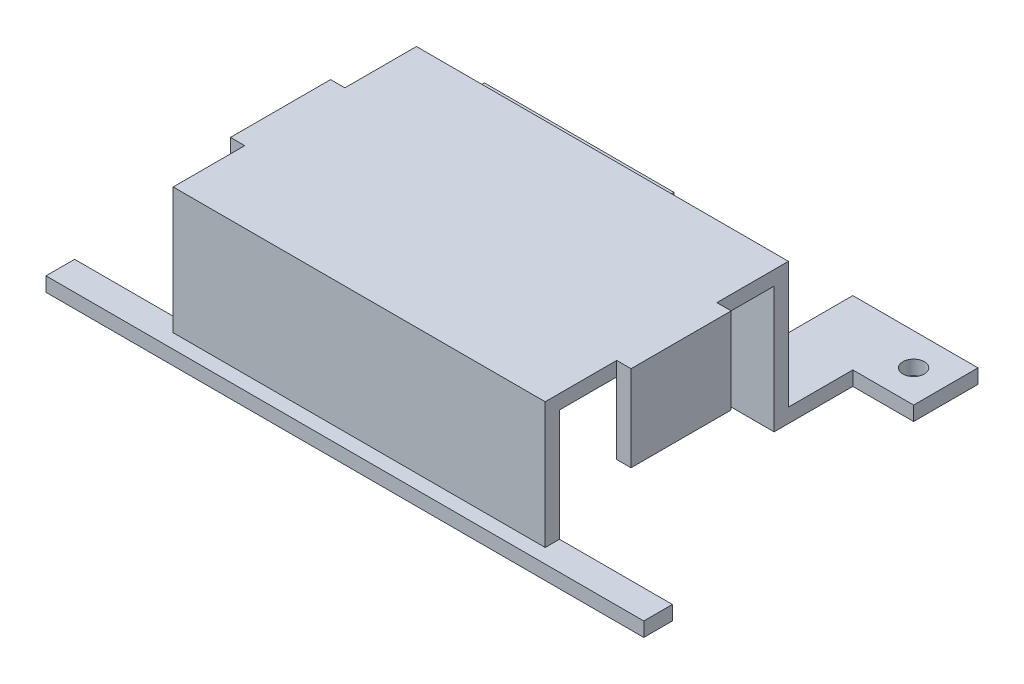
SolidWorks part; units mm, degrees
ref_plane "Front Plane" through (0, 0, 0) normal (0, 0, 1) x (1, 0, 0)
ref_plane "Top Plane" through (0, 0, 0) normal (0, 1, 0) x (1, 0, 0)
ref_plane "Right Plane" through (0, 0, 0) normal (1, 0, 0) x (0, 0, -1)
sketch "Sketch1" plane through (0, 0, 0) normal (0, 1, 0) x (1, 0, 0)
  line L1 (0, 0) -> (52, 0)
  line L2 (0, 0) -> (0, 34)
  line L3 (0, 34) -> (52, 34)
  line L4 (52, 0) -> (52, 34)
  dimension "D1" = 52
  dimension "D2" = 34
extrude "Boss-Extrude1" add sketch "Sketch1" along normal blind 19.65
sketch "Sketch2" plane through (0, 0, 0) normal (0, -1, 0) x (-1, 0, 0)
  line L0 (-52, 0) -> (-52, 34) construction
  line L1 (-52, 2) -> (0, 2)
  line L2 (-52, 2) -> (-52, 32)
  line L3 (-52, 32) -> (0, 32)
  line L4 (0, 2) -> (0, 32)
  line L5 (0, 34) -> (0, 0) construction
  line L6 (0, 0) -> (-52, 0) construction
  line L7 (-52, 34) -> (0, 34) construction
  dimension "D1" = 2
  dimension "D2" = 2
extrude "Cut-Extrude1" cut sketch "Sketch2" against normal blind 17.65
sketch "Sketch3" plane through (0, 0, -34) normal (0, 0, -1) x (-1, 0, 0)
  line L1 (-52, 0) -> (-43, 0)
  line L2 (-52, 0) -> (-52, 2)
  line L3 (-52, 2) -> (-43, 2)
  line L4 (-43, 0) -> (-43, 2)
  line L5 (0, 0) -> (-18, 0)
  line L6 (0, 0) -> (0, 2)
  line L7 (0, 2) -> (-18, 2)
  line L8 (-18, 0) -> (-18, 2)
  dimension "D1" = 9
  dimension "D2" = 2
  dimension "D3" = 18
  dimension "D4" = 2
extrude "Boss-Extrude2" add sketch "Sketch3" along normal blind 18
sketch "Sketch4" plane through (52, 0, 0) normal (1, 0, 0) x (0, 0, -1)
  line L0 (52, 2) -> (52, 0) construction
  line L1 (34, 2) -> (52, 2)
  line L2 (34, 2) -> (34, 0)
  line L3 (34, 0) -> (52, 0)
  line L4 (52, 2) -> (52, 0)
  line L5 (32, 0) -> (52, 0) construction
extrude "Boss-Extrude3" add sketch "Sketch4" along normal blind 8.5
sketch "Sketch5" plane through (0, 0, 0) normal (-1, 0, 0) x (0, 0, 1)
  line L1 (-34, 2) -> (-52, 2)
  line L2 (-34, 2) -> (-34, 0)
  line L3 (-34, 0) -> (-52, 0)
  line L4 (-52, 2) -> (-52, 0)
extrude "Boss-Extrude4" add sketch "Sketch5" along normal blind 8.5
sketch "Sketch6" plane through (0, 2, 0) normal (0, 1, 0) x (1, 0, 0)
  line L0 (-8.5, 34) -> (-8.5, 52) construction
  line L1 (-8.5, 52) -> (18, 52) construction
  line L2 (43, 52) -> (60.5, 52) construction
  line L3 (60.5, 52) -> (60.5, 34) construction
  circle A0 centre (56, 47.5) radius 1.5
  circle A1 centre (-4, 47.5) radius 1.5
  dimension "D1" = 3
  dimension "D2" = 3
  dimension "D3" = 4.5
  dimension "D4" = 4.5
  dimension "D5" = 4.5
  dimension "D6" = 4.5
extrude "Cut-Extrude2" cut sketch "Sketch6" against normal through all
sketch "Sketch7" plane through (0, 0, 0) normal (0, 0, 1) x (1, 0, 0)
  line L0 (0, 19.65) -> (0, 0) construction
  line L1 (0, 2) -> (52, 2)
  line L2 (0, 2) -> (0, 0)
  line L3 (0, 0) -> (52, 0)
  line L4 (52, 2) -> (52, 0)
  dimension "D1" = 2
extrude "Boss-Extrude5" add sketch "Sketch7" along normal blind 2
sketch "Sketch8" plane through (0, 0, 0) normal (-1, 0, 0) x (0, 0, 1)
  line L0 (-2, 0) -> (2, 0) construction
  line L1 (2, 2) -> (-2, 2)
  line L2 (2, 2) -> (2, 0)
  line L3 (2, 0) -> (-2, 0)
  line L4 (-2, 2) -> (-2, 0)
extrude "Boss-Extrude6" add sketch "Sketch8" along normal blind 15.78
sketch "Sketch9" plane through (52, 0, 0) normal (1, 0, 0) x (0, 0, -1)
  line L1 (-2, 2) -> (2, 2)
  line L2 (-2, 2) -> (-2, 0)
  line L3 (-2, 0) -> (2, 0)
  line L4 (2, 2) -> (2, 0)
extrude "Boss-Extrude7" add sketch "Sketch9" along normal blind 15.78
sketch "Sketch11" plane through (-8.5, 0, 0) normal (-1, 0, 0) x (0, 0, 1)
  line L1 (-43, 17.65) -> (-32, 17.65)
  line L2 (-43, 17.65) -> (-43, 0)
  line L3 (-43, 0) -> (-32, 0)
  line L4 (-32, 17.65) -> (-32, 0)
  dimension "D1" = 11
  dimension "D2" = 17.65
  dimension "D3" = 9
extrude "Cut-Extrude3" cut sketch "Sketch11" against normal blind 18
sketch "Sketch12" plane through (60.5, 0, 0) normal (1, 0, 0) x (0, 0, -1)
  line L0 (52, 2) -> (34, 2) construction
  line L1 (43, 2) -> (34, 2)
  line L2 (43, 2) -> (43, 0)
  line L3 (43, 0) -> (34, 0)
  line L4 (34, 2) -> (34, 0)
extrude "Cut-Extrude4" cut sketch "Sketch12" against normal blind 8.5
sketch "Sketch14" plane through (0, 0, 0) normal (-1, 0, 0) x (0, 0, 1)
  line L0 (-34, 19.65) -> (0, 19.65) construction
  line L1 (-24, 19.65) -> (-10, 19.65)
  line L2 (-24, 19.65) -> (-24, 17.65)
  line L3 (-24, 17.65) -> (-10, 17.65)
  line L4 (-10, 19.65) -> (-10, 17.65)
  line L5 (-2, 17.65) -> (-34, 17.65) construction
  line L7 (0, 19.65) -> (0, 2) construction
  line L8 (-34, 19.65) -> (-34, 17.65) construction
  point P10 (-10, 18.65)
  point P13 (-34, 18.65)
  dimension "D1" = 10
  dimension "D2" = 10
extrude "Boss-Extrude8" add sketch "Sketch14" along normal blind 2
sketch "Sketch15" plane through (52, 0, 0) normal (1, 0, 0) x (0, 0, -1)
  line L0 (32, 17.65) -> (2, 17.65) construction
  line L1 (24, 17.65) -> (10, 17.65)
  line L2 (24, 17.65) -> (24, 19.65)
  line L3 (24, 19.65) -> (10, 19.65)
  line L4 (10, 17.65) -> (10, 19.65)
  line L5 (0, 19.65) -> (34, 19.65) construction
  line L6 (34, 19.65) -> (34, 2) construction
  dimension "D1" = 10
  dimension "D2" = 10
extrude "Boss-Extrude9" add sketch "Sketch15" along normal blind 2
sketch "Sketch16" plane through (0, 17.65, 0) normal (0, -1, 0) x (-1, 0, 0)
  line L1 (0, 24) -> (2, 24)
  line L2 (0, 24) -> (0, 10)
  line L3 (0, 10) -> (2, 10)
  line L4 (2, 24) -> (2, 10)
  line L5 (-52, 24) -> (-54, 24)
  line L6 (-52, 24) -> (-52, 10)
  line L7 (-52, 10) -> (-54, 10)
  line L8 (-54, 24) -> (-54, 10)
extrude "Boss-Extrude10" add sketch "Sketch16" along normal blind 10
